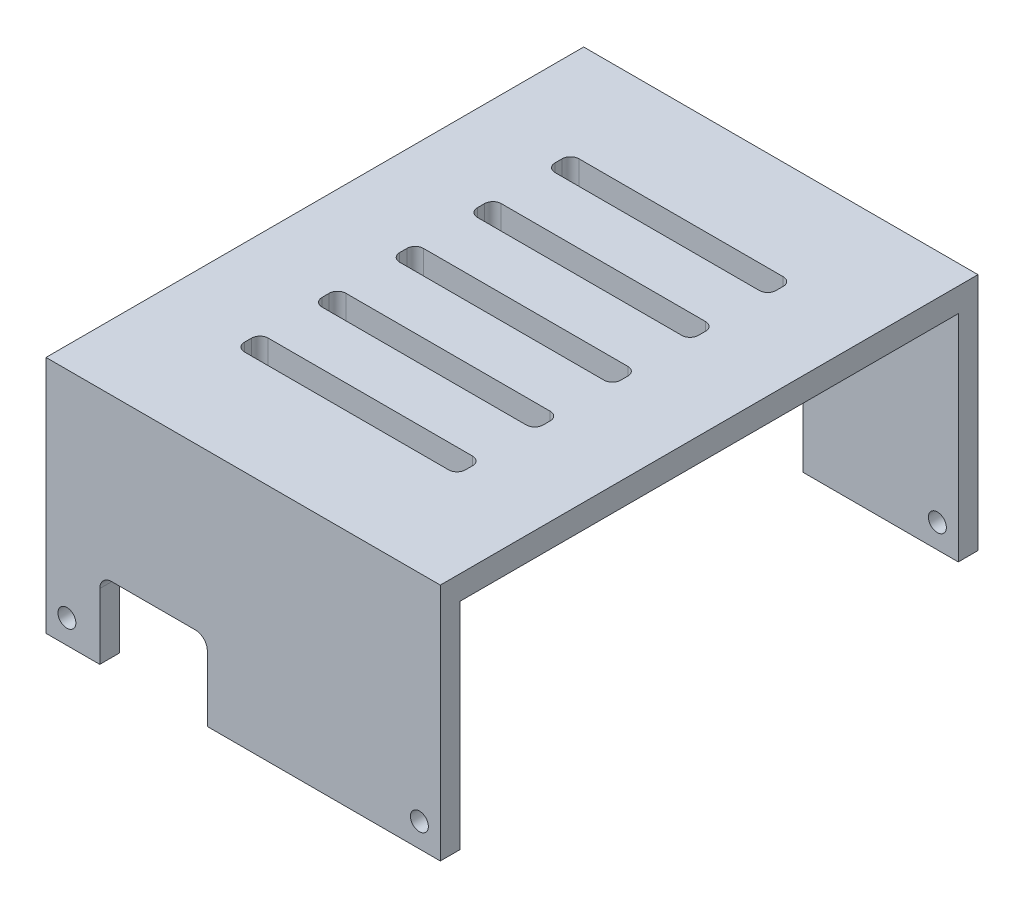
SolidWorks part; units mm, degrees
ref_plane "Front Plane" through (0, 0, 0) normal (0, 0, 1) x (1, 0, 0)
ref_plane "Top Plane" through (0, 0, 0) normal (0, 1, 0) x (1, 0, 0)
ref_plane "Right Plane" through (0, 0, 0) normal (1, 0, 0) x (0, 0, -1)
sketch "Sketch1" plane through (0, 0, 0) normal (0, 0, 1) x (1, 0, 0)
  line L1 (-33, -2) -> (33, -2)
  line L2 (-33, -2) -> (-33, 2)
  line L3 (-33, 2) -> (33, 2)
  line L4 (33, -2) -> (33, 2)
  line L5 (-33, -2) -> (33, 2) construction
  line L6 (-33, 2) -> (33, -2) construction
  point P0 (0, 0)
  dimension "D1" = 66
  dimension "D2" = 4
extrude "Boss-Extrude1" add sketch "Sketch1" along normal blind 90
sketch "Sketch2" plane through (0, 0, 90) normal (0, 0, 1) x (1, 0, 0)
  line L0 (-33, -2) -> (33, -2) construction
  line L1 (-33, -2) -> (33, -2)
  line L2 (-33, -2) -> (-33, -38)
  line L3 (-33, -38) -> (33, -38)
  line L4 (33, -2) -> (33, -38)
  dimension "D3" = 36
extrude "Boss-Extrude2" add sketch "Sketch2" against normal blind 3.3
sketch "Sketch3" plane through (0, 0, 0) normal (0, 0, -1) x (-1, 0, 0)
  line L4 (33, -38) -> (33, -2)
  line L5 (33, -2) -> (-33, -2)
  line L6 (-33, -2) -> (-33, -38)
  line L7 (-33, -38) -> (33, -38)
  line L8 (33, -38) -> (33, -2)
  line L9 (33, -2) -> (-33, -2)
  line L10 (-33, -2) -> (-33, -38)
  line L11 (-33, -38) -> (33, -38)
  dimension "D1" = 0
extrude "Boss-Extrude3" add sketch "Sketch3" against normal blind 3.3
sketch "Sketch4" plane through (0, 0, 90) normal (0, 0, 1) x (1, 0, 0)
  line L0 (-33, -38) -> (33, -38) construction
  line L1 (-33, 2) -> (-33, -38) construction
  line L2 (33, -38) -> (33, 2) construction
  circle A0 centre (-29.5, -34) radius 1.5
  circle A1 centre (29.5, -34) radius 1.5
  dimension "D1" = 3
  dimension "D3" = 3.5
  dimension "D5" = 3
  dimension "D2" = 4
  dimension "D4" = 3.5
extrude "Cut-Extrude1" cut sketch "Sketch4" against normal through all
sketch "Sketch5" plane through (0, 0, 90) normal (0, 0, 1) x (1, 0, 0)
  line L0 (-15, -25) -> (-15, -38) construction
  line L1 (-24, -25) -> (-6, -25)
  line L2 (-24, -25) -> (-24, -38)
  line L3 (-24, -38) -> (-6, -38)
  line L4 (-6, -25) -> (-6, -38)
  line L5 (33, -38) -> (33, 2) construction
  line L6 (-33, -38) -> (33, -38) construction
  dimension "D1" = 18
  dimension "D2" = 48
  dimension "D3" = 13
extrude "Cut-Extrude2" cut sketch "Sketch5" against normal up to next
sketch "Sketch7" plane through (0, 0, 0) normal (0, 0, -1) x (-1, 0, 0)
  line L0 (-33, -38) -> (33, -38) construction
  line L1 (-7, -38) -> (23, -38)
  line L2 (-7, -38) -> (-7, -21)
  line L3 (-4, -18) -> (20, -18)
  line L4 (23, -38) -> (23, -21)
  line L5 (33, 2) -> (33, -38) construction
  arc A0 (20, -18) -> (23, -21) centre (20, -21) cw
  arc A1 (-4, -18) -> (-7, -21) centre (-4, -21) ccw
  point P10 (23, -18)
  point P13 (-7, -18)
  dimension "D4" = 3
  dimension "D1" = 30
  dimension "D2" = 20
  dimension "D3" = 10
extrude "Cut-Extrude4" cut sketch "Sketch7" against normal up to next
fillet "Fillet1" radius 2 2 edges at (-24, -25, 88.35) (-6, -25, 88.35)
sketch "Sketch8" plane through (0, 2, 0) normal (0, 1, 0) x (1, 0, 0)
  line L0 (33, 0) -> (-33, 0) construction
  line L1 (-17.2, -16.6) -> (17, -16.6)
  line L2 (-18.6, -18) -> (-18.6, -19.2)
  line L3 (-17.2, -20.6) -> (17, -20.6)
  line L4 (18.4, -18) -> (18.4, -19.2)
  line L5 (-33, -90) -> (-33, 0) construction
  line L6 (33, -90) -> (33, 0) construction
  arc A0 (18.4, -19.2) -> (17, -20.6) centre (17, -19.2) cw
  arc A1 (18.4, -18) -> (17, -16.6) centre (17, -18) ccw
  arc A2 (-17.2, -20.6) -> (-18.6, -19.2) centre (-17.2, -19.2) cw
  arc A3 (-17.2, -16.6) -> (-18.6, -18) centre (-17.2, -18) ccw
  point P9 (18.4, -20.6)
  point P12 (18.4, -16.6)
  point P17 (-18.6, -16.6)
  dimension "D4" = 1.4
  dimension "D1" = 90
  dimension "D2" = 4
  dimension "D3" = 37
  dimension "D5" = 18
  dimension "D6" = 16
extrude "Cut-Extrude5" cut sketch "Sketch8" against normal up to next
pattern_linear "LPattern1" count 5 spacing 13 along (0, 0, 1) of "Cut-Extrude5"
